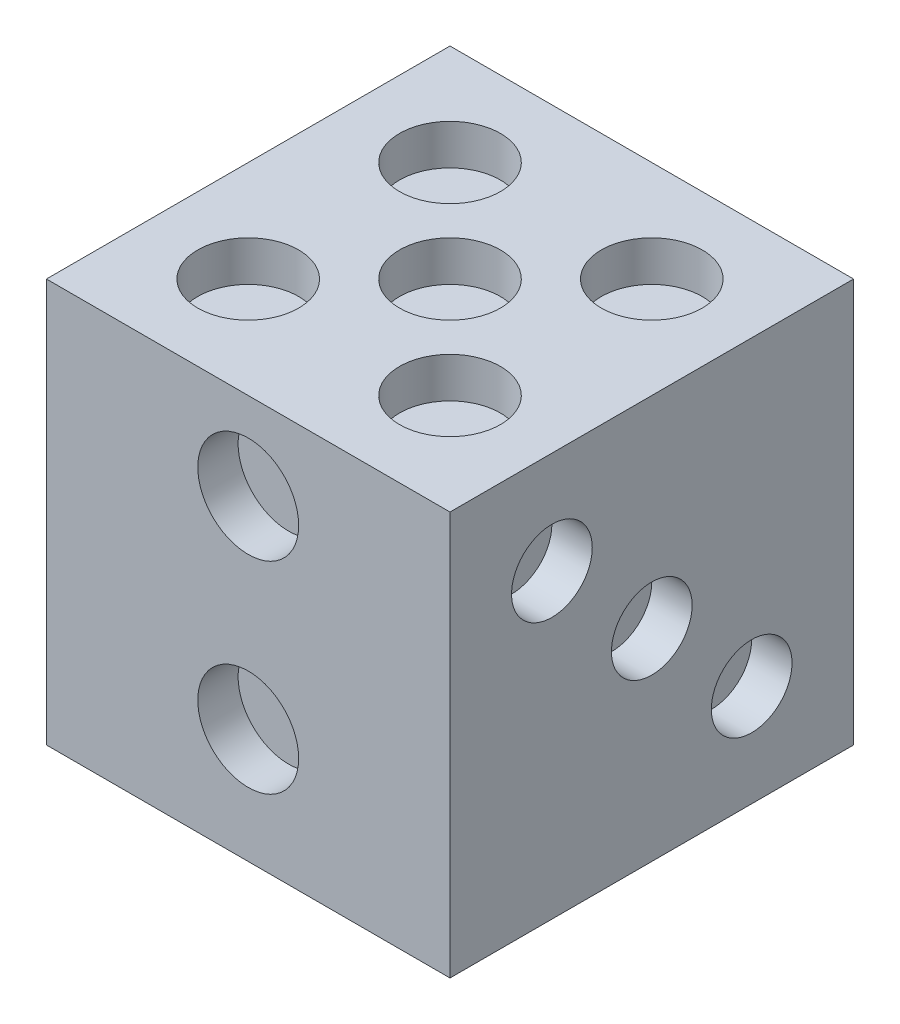
SolidWorks part; units mm, degrees
ref_plane "Front Plane" through (0, 0, 0) normal (0, 0, 1) x (1, 0, 0)
ref_plane "Top Plane" through (0, 0, 0) normal (0, 1, 0) x (1, 0, 0)
ref_plane "Right Plane" through (0, 0, 0) normal (1, 0, 0) x (0, 0, -1)
sketch "Sketch1" plane through (0, 0, 0) normal (0, 1, 0) x (1, 0, 0)
  line L1 (-40.9404, -52.2269) -> (59.0596, -52.2269)
  line L2 (-40.9404, -52.2269) -> (-40.9404, 47.7731)
  line L3 (-40.9404, 47.7731) -> (59.0596, 47.7731)
  line L4 (59.0596, -52.2269) -> (59.0596, 47.7731)
  line L5 (-40.9404, -52.2269) -> (59.0596, 47.7731) construction
  line L6 (-40.9404, 47.7731) -> (59.0596, -52.2269) construction
  point P0 (9.0596, -2.2269)
  dimension "D1" = 100
  dimension "D2" = 100
  dimension "D3" = 50
  dimension "D4" = 50
extrude "Boss-Extrude1" add sketch "Sketch1" along normal blind 100 contours L3 L4 L1 L2
sketch "Sketch2" plane through (0, 0, 0) normal (0, -1, 0) x (1, 0, 0)
  circle A0 centre (10.5377, 2.7056) radius 15
  point P2 (0, 0)
  point P3 (0, 0)
  point P4 (9.7841, 5.8783)
  point P5 (0, 0)
  point P6 (0, 0)
  point P7 (10.5377, 2.7056)
  dimension "D1" = 30
extrude "Cut-Extrude2" cut sketch "Sketch2" against normal blind 10 contours A0
sketch "Sketch3" plane through (59.0596, 0, 0) normal (1, 0, 0) x (0, 0, -1)
  line L0 (47.7731, 0) -> (-52.2269, 100) construction
  circle A0 centre (-2.2269, 50) radius 10
  circle A1 centre (22.5218, 25.2513) radius 10
  circle A2 centre (-26.9756, 74.7487) radius 10
  point P10 (0, 0)
  point P11 (0, 0)
  point P12 (0, 0)
  dimension "D1" = 20
  dimension "D2" = 35
  dimension "D3" = 35
extrude "Cut-Extrude3" cut sketch "Sketch3" against normal blind 10
sketch "Sketch5" plane through (0, 0, -47.7731) normal (0, 0, -1) x (-1, 0, 0)
  line L0 (40.9404, 100) -> (40.9404, 0) construction
  line L1 (-59.0596, 100) -> (40.9404, 100) construction
  line L2 (-59.0596, 100) -> (-59.0596, 0) construction
  line L3 (-59.0596, 0) -> (40.9404, 0) construction
  line L4 (40.9404, 100) -> (40.9404, 0) construction
  line L5 (-59.0596, 100) -> (40.9404, 0) construction
  line L6 (-59.0596, 0) -> (40.9404, 100) construction
  line L8 (15.9404, 75) -> (-34.0596, 75)
  line L9 (15.9404, 75) -> (15.9404, 25)
  line L10 (15.9404, 25) -> (-34.0596, 25)
  line L11 (-34.0596, 75) -> (-34.0596, 25)
  line L12 (15.9404, 75) -> (-34.0596, 25) construction
  line L13 (15.9404, 25) -> (-34.0596, 75) construction
  circle A0 centre (-34.0596, 25) radius 12.5
  circle A1 centre (-34.0596, 75) radius 12.5
  circle A2 centre (15.9404, 25) radius 12.5
  circle A3 centre (15.9404, 75) radius 12.5
  point P0 (-9.0596, 50)
  point P10 (-9.0596, 50)
  point P17 (0, 0)
  dimension "D1" = 25
sketch "Sketch7" plane through (0, 0, -47.7731) normal (0, 0, -1) x (-1, 0, 0)
extrude "Cut-Extrude5" cut sketch "Sketch5" against normal blind 10 contours L8 A1 L11 | L11 A1 L8 | L9 A3 L8 | L8 A3 L9 | L11 A0 L10 | L10 A0 L11 | L10 A2 L9 | L9 A2 L10
sketch "Sketch11" plane through (0, 100, 0) normal (0, 1, 0) x (1, 0, 0)
  line L1 (59.0596, 47.7731) -> (-40.9404, 47.7731) construction
  line L2 (59.0596, 47.7731) -> (59.0596, -52.2269) construction
  line L3 (59.0596, -52.2269) -> (-40.9404, -52.2269) construction
  line L4 (-40.9404, 47.7731) -> (-40.9404, -52.2269) construction
  line L5 (59.0596, 47.7731) -> (-40.9404, -52.2269) construction
  line L6 (59.0596, -52.2269) -> (-40.9404, 47.7731) construction
  line L7 (-15.9404, 22.7731) -> (34.0596, 22.7731) construction
  line L8 (-15.9404, 22.7731) -> (-15.9404, -27.2269) construction
  line L9 (-15.9404, -27.2269) -> (34.0596, -27.2269) construction
  line L10 (34.0596, 22.7731) -> (34.0596, -27.2269) construction
  line L11 (-15.9404, 22.7731) -> (34.0596, -27.2269) construction
  line L12 (-15.9404, -27.2269) -> (34.0596, 22.7731) construction
  circle A0 centre (34.0596, 22.7731) radius 12.5
  circle A1 centre (34.0596, -27.2269) radius 12.5
  circle A2 centre (-15.9404, -27.2269) radius 12.5
  circle A3 centre (-15.9404, 22.7731) radius 12.5
  circle A4 centre (9.0596, -2.2269) radius 12.5
  point P0 (9.0596, -2.2269)
  point P5 (34.0596, -2.2269)
  point P7 (-15.9404, -2.2269)
  point P9 (9.0596, -2.2269)
  dimension "D1" = 25
extrude "Cut-Extrude6" cut sketch "Sketch11" against normal blind 10 contours A1 | A0 | A4 | A3 | A2
sketch "Sketch12" plane through (0, 0, 52.2269) normal (0, 0, 1) x (1, 0, 0)
  line L0 (9.0596, 100) -> (9.0596, 0) construction
  line L1 (-40.9404, 100) -> (59.0596, 100) construction
  line L2 (-40.9404, 0) -> (59.0596, 0) construction
  circle A0 centre (9.0596, 78.3885) radius 12.5
  circle A1 centre (9.0596, 28.3885) radius 12.5
  dimension "D1" = 25
  dimension "D2" = 50
extrude "Cut-Extrude7" cut sketch "Sketch12" against normal blind 10
sketch "Sketch13" plane through (-40.9404, 0, 0) normal (-1, 0, 0) x (0, 0, 1)
  line L0 (52.2269, 100) -> (52.2269, 0) construction
  line L1 (52.2269, 100) -> (-47.7731, 100) construction
  line L2 (52.2269, 100) -> (52.2269, 0) construction
  line L3 (52.2269, 0) -> (-47.7731, 0) construction
  line L4 (-47.7731, 100) -> (-47.7731, 0) construction
  line L5 (52.2269, 100) -> (-47.7731, 0) construction
  line L6 (52.2269, 0) -> (-47.7731, 100) construction
  line L7 (52.2269, 0) -> (-47.7731, 0) construction
  line L8 (52.2269, 100) -> (-47.7731, 100) construction
  line L9 (2.2269, 25) -> (2.2269, 75) construction
  line L11 (27.2269, 75) -> (-22.7731, 75) construction
  line L12 (27.2269, 75) -> (27.2269, 25) construction
  line L13 (27.2269, 25) -> (-22.7731, 25) construction
  line L14 (-22.7731, 75) -> (-22.7731, 25) construction
  line L15 (27.2269, 75) -> (-22.7731, 25) construction
  line L16 (27.2269, 25) -> (-22.7731, 75) construction
  circle A0 centre (-22.7731, 25) radius 12
  circle A1 centre (-22.7731, 73.7094) radius 12
  circle A2 centre (2.2269, 75) radius 12
  circle A3 centre (2.2269, 25) radius 12
  circle A4 centre (27.2269, 25) radius 12
  circle A5 centre (27.2269, 75) radius 12
  point P0 (2.2269, 50)
  point P17 (2.2269, 50)
  dimension "D1" = 24
sketch "Sketch14" plane through (-40.9404, 0, 0) normal (-1, 0, 0) x (0, 0, 1)
extrude "Cut-Extrude12" cut sketch "Sketch13" against normal blind 10 contours A0 | A3 | A4 | A5 | A2 | A1
